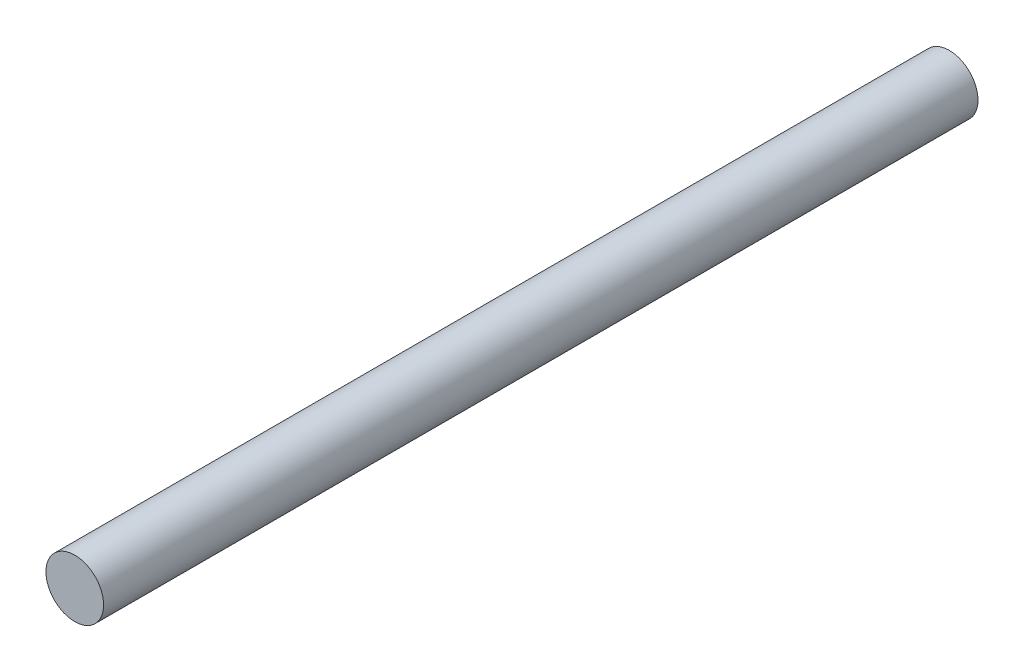
SolidWorks part; units mm, degrees
ref_plane "Front Plane" through (0, 0, 0) normal (0, 0, 1) x (1, 0, 0)
ref_plane "Top Plane" through (0, 0, 0) normal (0, 1, 0) x (1, 0, 0)
ref_plane "Right Plane" through (0, 0, 0) normal (1, 0, 0) x (0, 0, -1)
sketch "Sketch1" plane through (0, 0, 0) normal (0, 0, 1) x (1, 0, 0)
  circle A0 centre (0, 0) radius 3
  dimension "D1" = 6
extrude "Boss-Extrude1" add sketch "Sketch1" along normal blind 91
